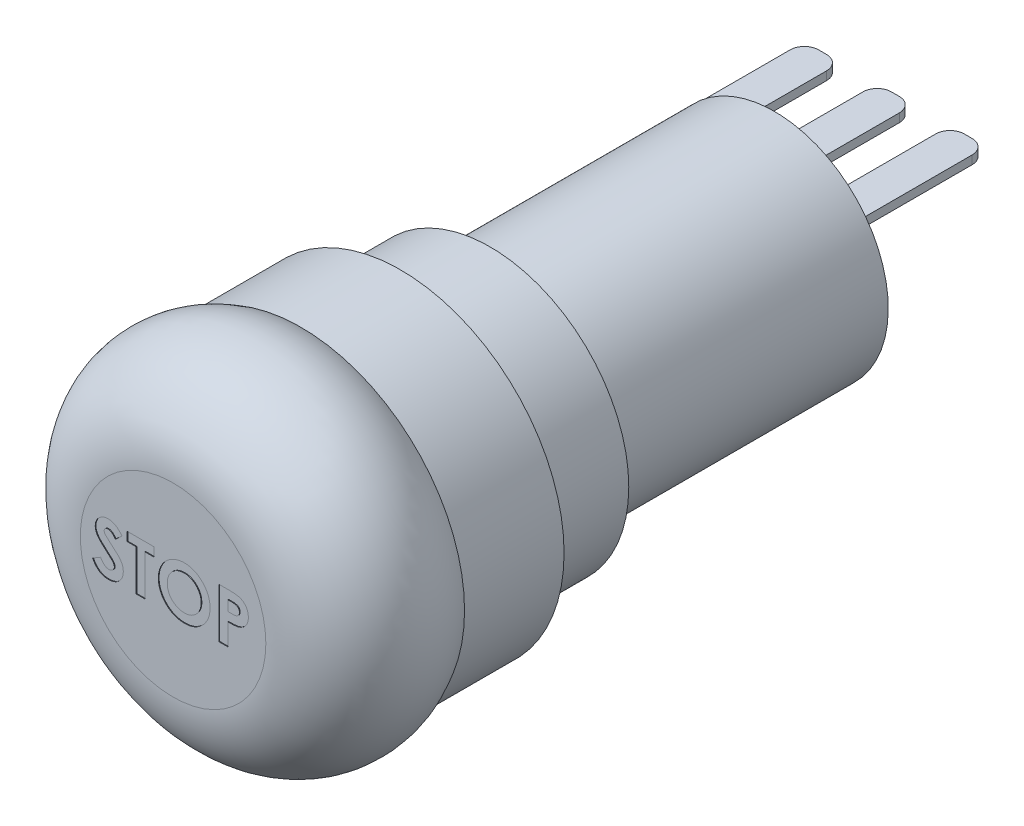
SolidWorks part; units mm, degrees
ref_plane "Plan de face" through (0, 0, 0) normal (0, 0, 1) x (1, 0, 0)
ref_plane "Plan de dessus" through (0, 0, 0) normal (0, 1, 0) x (1, 0, 0)
ref_plane "Plan de droite" through (0, 0, 0) normal (1, 0, 0) x (0, 0, -1)
sketch "Esquisse1" plane through (0, 0, 0) normal (0, 0, 1) x (1, 0, 0)
  circle A0 centre (0, 0) radius 8
  dimension "D1" = 16
extrude "Boss.-Extru.1" add sketch "Esquisse1" along normal blind 20
sketch "Esquisse2" plane through (0, 0, 20) normal (0, 0, 1) x (1, 0, 0)
  circle A0 centre (0, 0) radius 9.75
  dimension "D1" = 19.5
extrude "Boss.-Extru.2" add sketch "Esquisse2" along normal blind 6.3
sketch "Esquisse3" plane through (0, 0, 0) normal (0, 1, 0) x (1, 0, 0)
  line L0 (0, -26.3) -> (-11.5, -26.3)
  line L1 (-9.75, -26.3) -> (9.75, -26.3) construction
  line L2 (-11.5, -26.3) -> (-11.5, -33.3)
  line L3 (-6.5249, -42.3) -> (0, -42.3)
  line L4 (0, -42.3) -> (0, -26.3)
  arc A0 (-11.5, -33.3) -> (-6.5249, -42.3) centre (-6.5249, -36.4249) ccw
  point P7 (0, 0)
  point P8 (-12.4, -36.4249)
  dimension "D1" = 16
  dimension "D3" = 12.4
  dimension "D2" = 11.5
  dimension "D4" = 7
ref_axis "Axe1" through (0, 0, 20) along (0, 0, -1)
revolve "Révolution1" add sketch "Esquisse3" angle 360 about axis through (0, 0, 20) along (0, 0, -1)
sketch "Esquisse4" plane through (0, 0, 0) normal (0, 0, -1) x (-1, 0, 0)
  line L1 (-6.4, 4.8) -> (6.4, 4.8)
  line L2 (-6.4, 4.8) -> (-6.4, 4.2)
  line L3 (-6.4, 4.2) -> (6.4, 4.2)
  line L4 (6.4, 4.8) -> (6.4, 4.2)
  circle A0 centre (0, 0) radius 8 construction
  circle A1 centre (0, 0) radius 8 construction
  point P4 (0, 0)
  point P5 (0, 0)
  point P8 (0, 0)
  dimension "D1" = 0.6
  dimension "D2" = 12.8
extrude "Boss.-Extru.3" add sketch "Esquisse4" along normal blind 8.5
sketch "Esquisse5" plane through (0, 0, 42.3) normal (0, 0, 1) x (1, 0, 0)
  line L0 (-5.79, -1.5398) -> (5.4083, -1.5398) construction
  text T0 "<b>STOP</b>"
  point P3 (5.4083, -1.5398)
extrude "Enlèv. mat.-Extru.1" cut sketch "Esquisse5" against normal blind 0.05
sketch "Esquisse6" plane through (0, 4.2, 0) normal (0, -1, 0) x (1, 0, 0)
  line L0 (-8, 0) -> (8, 0) construction
  line L1 (-1.28, 0) -> (-3.84, 0)
  line L2 (-1.28, 0) -> (-1.28, -8.5)
  line L3 (-1.28, -8.5) -> (-3.84, -8.5)
  line L4 (-3.84, 0) -> (-3.84, -8.5)
  line L5 (6.4, -8.5) -> (-6.4, -8.5) construction
  line L6 (-1.28, 0) -> (1.28, 0) construction
  line L7 (3.84, 0) -> (1.28, 0)
  line L8 (3.84, 0) -> (3.84, -8.5)
  line L9 (3.84, -8.5) -> (1.28, -8.5)
  line L10 (1.28, 0) -> (1.28, -8.5)
  line L11 (-6.4, -8.5) -> (-6.4, 0) construction
  line L12 (-3.84, 0) -> (-6.4, 0) construction
  line L13 (6.4, 0) -> (-6.4, 0) construction
  line L14 (3.84, 0) -> (6.4, 0) construction
  point P20 (0, 0)
extrude "Enlèv. mat.-Extru.2" cut sketch "Esquisse6" against normal through all
fillet "Congé1" radius 1 6 edges at (6.4, 4.5, -8.5) (3.84, 4.5, -8.5) (1.28, 4.5, -8.5) (-1.28, 4.5, -8.5) (-3.84, 4.5, -8.5) (-6.4, 4.5, -8.5)
